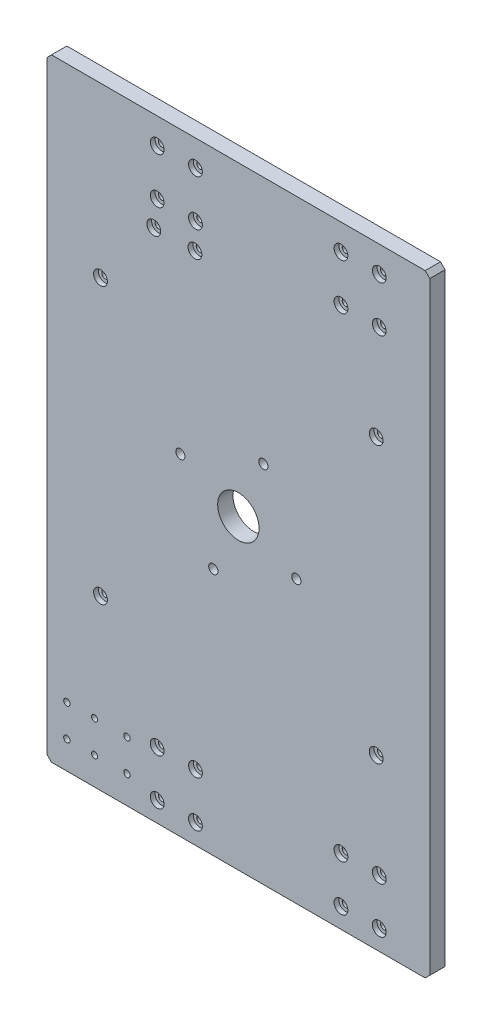
SolidWorks part; units mm, degrees
ref_plane "Plan de face" through (0, 0, 0) normal (0, 0, 1) x (1, 0, 0)
ref_plane "Plan de dessus" through (0, 0, 0) normal (0, 1, 0) x (1, 0, 0)
ref_plane "Plan de droite" through (0, 0, 0) normal (1, 0, 0) x (0, 0, -1)
sketch "Esquisse1" plane through (0, 0, 0) normal (0, 0, 1) x (1, 0, 0)
  line L1 (-125, -200) -> (125, -200)
  line L2 (-125, -200) -> (-125, 200)
  line L3 (-125, 200) -> (125, 200)
  line L4 (125, -200) -> (125, 200)
  line L5 (-125, -200) -> (125, 200) construction
  line L6 (-125, 200) -> (125, -200) construction
  point P0 (0, 0)
  dimension "D1" = 400
  dimension "D2" = 250
extrude "Boss.-Extru.1" add sketch "Esquisse1" along normal blind 10
ref_plane "Plan1" through (0, 0, 0) normal (1, 0, 0) x (0, 0, -1)
ref_plane "Plan2" through (0, 0, 0) normal (0, 1, 0) x (1, 0, 0)
sketch "Esquisse2" plane through (0, 0, 0) normal (0, 0, -1) x (-1, 0, 0)
  circle A0 centre (0, 0) radius 13.5
  dimension "D1" = 27
extrude "Enlèv. mat.-Extru.1" cut sketch "Esquisse2" against normal through all
chamfer "Chanfrein1" distance 3 angle 45 4 edges at (-125, -200, 5) (125, -200, 5) (125, 200, 5) (-125, 200, 5)
hole_wizard "Trou taraudé M51" positions "Esquisse6" profile "Esquisse5" tap size "M5" standard "ISO" end condition through all
sketch "Esquisse6" plane through (0, 0, 10) normal (0, 0, 1) x (1, 0, 0)
  point P0 (-72.6985, -161.0797)
  point P3 (-72.6985, -181.8387)
  point P6 (-111.9372, -181.8387)
  point P9 (-111.9372, -161.0797)
sketch "Esquisse5" plane through (-72.6985, -161.0797, 10) normal (1, 0, 0) x (0, -1, 0)
  line L0 (0, 0) -> (0, 10)
  line L1 (0, 10) -> (2.1, 10)
  line L2 (2.1, 10) -> (2.1, 0)
  line L5 (2.1, 0) -> (0, 0)
  line L11 (0, -6.35) -> (0, 107.95) construction
  dimension "Diamètre du trou pour taraudage jusqu'au prochain" = 4.2
  dimension "Profondeur du trou pour taraudage jusqu'au prochain" = 10
cosmetic thread "Filetage de perçage3" parameters "D2"=5
cosmetic thread "Filetage de perçage4" parameters "D2"=5
cosmetic thread "Filetage de perçage5" parameters "D2"=5
cosmetic thread "Filetage de perçage6" parameters "D2"=5
hole_wizard "Trous de centrage Ø4.0mm2" positions "Esquisse9" profile "Esquisse8" hole size "Ø4.0" standard "ISO" end condition through all
sketch "Esquisse9" plane through (0, 0, 10) normal (0, 0, 1) x (1, 0, 0)
  point P0 (-93.8631, -161.0797)
  point P3 (-93.8631, -181.8387)
sketch "Esquisse8" plane through (-93.8631, -161.0797, 10) normal (1, 0, 0) x (0, -1, 0)
  line L0 (0, 0) -> (0, 10)
  line L1 (0, 10) -> (2, 10)
  line L2 (2, 10) -> (2, 0)
  line L5 (2, 0) -> (0, 0)
  line L11 (0, -6.35) -> (0, 107.95) construction
  dimension "Diamètre du perçage jusqu'au prochain" = 4
  dimension "Profondeur du perçage jusqu'au prochain" = 10
sketch "Esquisse10" plane through (0, 0, 10) normal (0, 0, 1) x (1, 0, 0)
  circle A0 centre (0, 0) radius 41.25 construction
  dimension "D1" = 82.5
hole_wizard "Trous de centrage Ø6.0mm2" positions "Esquisse26" profile "Esquisse25" hole size "Ø6.0" standard "ISO" end condition through all
sketch "Esquisse26" plane through (0, 0, 10) normal (0, 0, 1) x (1, 0, 0)
  point P0 (16.3571, 37.8683)
  point P2 (37.8683, -16.3571)
  point P4 (-16.3571, -37.8683)
  point P6 (-37.8683, 16.3571)
sketch "Esquisse25" plane through (16.3571, 37.8683, 10) normal (1, 0, 0) x (0, -1, 0)
  line L0 (0, 0) -> (0, 10)
  line L1 (0, 10) -> (3, 10)
  line L2 (3, 10) -> (3, 0)
  line L5 (3, 0) -> (0, 0)
  line L11 (0, -6.35) -> (0, 107.95) construction
  dimension "Diamètre du perçage jusqu'au prochain" = 6
  dimension "Profondeur du perçage jusqu'au prochain" = 10
hole_wizard "Dégagement M41" positions "Esquisse28" profile "Esquisse27" hole size "M4" standard "JIS" end condition through all
sketch "Esquisse28" plane through (0, 0, 0) normal (0, 0, -1) x (-1, 0, 0)
  point P0 (28, -187)
  point P2 (28, -157)
  point P4 (53, -157)
  point P6 (53, -187)
sketch "Esquisse27" plane through (-28, -187, 0) normal (1, 0, 0) x (0, 1, 0)
  line L0 (0, 0) -> (0, 10)
  line L1 (0, 10) -> (2.25, 10)
  line L2 (2.25, 10) -> (2.25, 0)
  line L5 (2.25, 0) -> (0, 0)
  line L11 (0, -6.35) -> (0, 107.95) construction
  dimension "Diamètre du perçage jusqu'au prochain" = 4.5
  dimension "Profondeur du perçage jusqu'au prochain" = 10
pattern_linear "Répétition linéaire1" count 2 spacing 120 along (1, 0, 0) count 2 spacing 340 along (0, 1, 0) of "Dégagement M41"
hole_wizard "Chambrage pour vis à tête ronde bombée M41" positions "Esquisse30" profile "Esquisse29" counterbore size "M4" standard "Ansi Metric" end condition through all
sketch "Esquisse30" plane through (0, 0, 10) normal (0, 0, 1) x (1, 0, 0)
  point P0 (92, -157)
sketch "Esquisse29" plane through (92, -157, 10) normal (1, 0, 0) x (0, -1, 0)
  line L0 (0, 0) -> (0, 10)
  line L1 (0, 10) -> (2.25, 10)
  line L2 (2.25, 3.125) -> (2.25, 10)
  line L3 (2.25, 3.125) -> (2.275, 3.1)
  line L4 (2.275, 3.1) -> (4.5, 3.1)
  line L5 (4.5, 3.1) -> (4.5, 0)
  line L7 (0, 0) -> (4.5, 0)
  line L9 (-2.25, 3.125) -> (-2.275, 3.1) construction
  line L11 (0, -6.35) -> (0, 107.95) construction
  dimension "Diamètre du perçage jusqu'au prochain" = 4.5
  dimension "Profondeur du perçage jusqu'au prochain" = 10
  dimension "Diamètre du chambrage" = 9
  dimension "Profondeur du chambrage" = 3.1
  dimension "Diamètre du fraisage milieu" = 4.55
  dimension "Angle du fraisage milieu" = 90
pattern_linear "Répétition linéaire2" count 2 spacing 30 along (0, -1, 0) count 2 spacing 25 along (-1, 0, 0) of "Chambrage pour vis à tête ronde bombée M41"
pattern_linear "Répétition linéaire3" count 2 spacing 120 along (-1, 0, 0) count 2 spacing 340 along (0, 1, 0) of "Répétition linéaire2", "Chambrage pour vis à tête ronde bombée M41"
hole_wizard "Dégagement M42" positions "Esquisse32" profile "Esquisse31" hole size "M4" standard "JIS" end condition through all
sketch "Esquisse32" plane through (0, 0, 0) normal (0, 0, -1) x (-1, 0, 0)
  point P0 (90, -90)
  point P2 (90, 90)
  point P4 (-90, 90)
  point P6 (-90, -90)
sketch "Esquisse31" plane through (-90, -90, 0) normal (1, 0, 0) x (0, 1, 0)
  line L0 (0, 0) -> (0, 10)
  line L1 (0, 10) -> (2.25, 10)
  line L2 (2.25, 10) -> (2.25, 0)
  line L5 (2.25, 0) -> (0, 0)
  line L11 (0, -6.35) -> (0, 107.95) construction
  dimension "Diamètre du perçage jusqu'au prochain" = 4.5
  dimension "Profondeur du perçage jusqu'au prochain" = 10
hole_wizard "Chambrage pour vis à tête ronde bombée M42" positions "Esquisse34" profile "Esquisse33" counterbore size "M4" standard "Ansi Metric" end condition through all
sketch "Esquisse34" plane through (0, 0, 10) normal (0, 0, 1) x (1, 0, 0)
  point P0 (-90, -90)
  point P2 (-90, 90)
  point P4 (90, -90)
  point P6 (90, 90)
sketch "Esquisse33" plane through (-90, -90, 10) normal (1, 0, 0) x (0, -1, 0)
  line L0 (0, 0) -> (0, 10)
  line L1 (0, 10) -> (2.25, 10)
  line L2 (2.25, 3.125) -> (2.25, 10)
  line L3 (2.25, 3.125) -> (2.275, 3.1)
  line L4 (2.275, 3.1) -> (4.5, 3.1)
  line L5 (4.5, 3.1) -> (4.5, 0)
  line L7 (0, 0) -> (4.5, 0)
  line L9 (-2.25, 3.125) -> (-2.275, 3.1) construction
  line L11 (0, -6.35) -> (0, 107.95) construction
  dimension "Diamètre du perçage jusqu'au prochain" = 4.5
  dimension "Profondeur du perçage jusqu'au prochain" = 10
  dimension "Diamètre du chambrage" = 9
  dimension "Profondeur du chambrage" = 3.1
  dimension "Diamètre du fraisage milieu" = 4.55
  dimension "Angle du fraisage milieu" = 90
hole_wizard "Dégagement M43" positions "Esquisse36" profile "Esquisse35" hole size "M4" standard "JIS" end condition through all
sketch "Esquisse36" plane through (0, 0, 0) normal (0, 0, -1) x (-1, 0, 0)
  point P0 (55.199, 135.7065)
  point P2 (28.3418, 135.9918)
sketch "Esquisse35" plane through (-55.199, 135.7065, 0) normal (1, 0, 0) x (0, 1, 0)
  line L0 (0, 0) -> (0, 10)
  line L1 (0, 10) -> (2.25, 10)
  line L2 (2.25, 10) -> (2.25, 0)
  line L5 (2.25, 0) -> (0, 0)
  line L11 (0, -6.35) -> (0, 107.95) construction
  dimension "Diamètre du perçage jusqu'au prochain" = 4.5
  dimension "Profondeur du perçage jusqu'au prochain" = 10
hole_wizard "Chambrage pour vis à tête ronde bombée M43" positions "Esquisse38" profile "Esquisse37" counterbore size "M4" standard "Ansi Metric" end condition through all
sketch "Esquisse38" plane through (0, 0, 10) normal (0, 0, 1) x (1, 0, 0)
  point P0 (-55.199, 135.7065)
  point P2 (-28.3418, 135.9918)
sketch "Esquisse37" plane through (-55.199, 135.7065, 10) normal (1, 0, 0) x (0, -1, 0)
  line L0 (0, 0) -> (0, 10)
  line L1 (0, 10) -> (2.25, 10)
  line L2 (2.25, 3.125) -> (2.25, 10)
  line L3 (2.25, 3.125) -> (2.275, 3.1)
  line L4 (2.275, 3.1) -> (4.5, 3.1)
  line L5 (4.5, 3.1) -> (4.5, 0)
  line L7 (0, 0) -> (4.5, 0)
  line L9 (-2.25, 3.125) -> (-2.275, 3.1) construction
  line L11 (0, -6.35) -> (0, 107.95) construction
  dimension "Diamètre du perçage jusqu'au prochain" = 4.5
  dimension "Profondeur du perçage jusqu'au prochain" = 10
  dimension "Diamètre du chambrage" = 9
  dimension "Profondeur du chambrage" = 3.1
  dimension "Diamètre du fraisage milieu" = 4.55
  dimension "Angle du fraisage milieu" = 90
